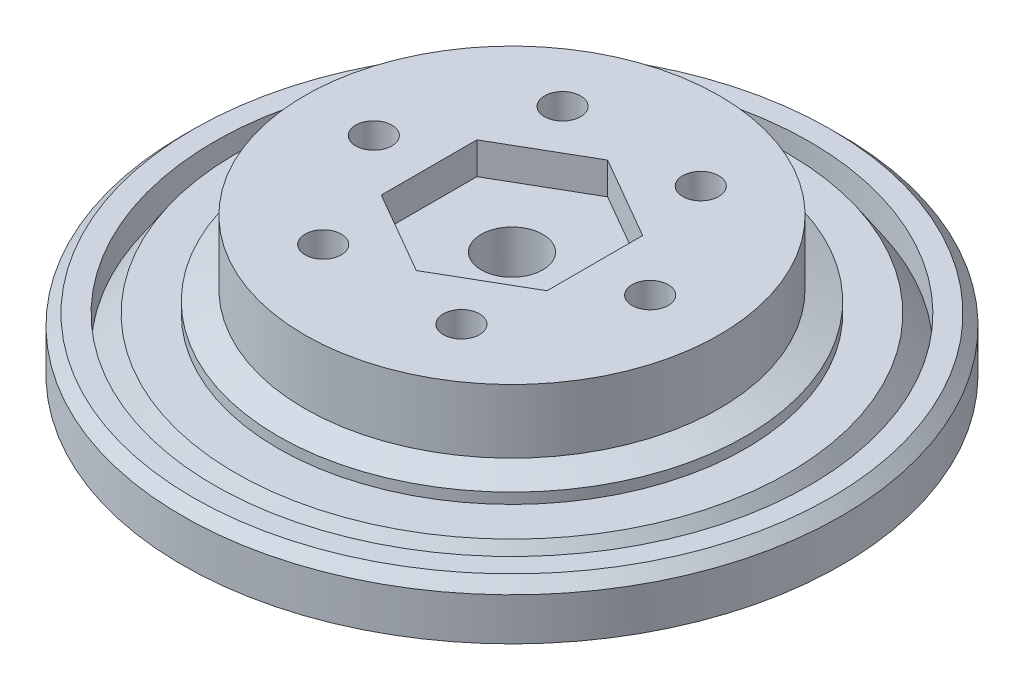
SolidWorks part; units mm, degrees
ref_plane "Спереди" through (0, 0, 0) normal (0, 0, 1) x (1, 0, 0)
ref_plane "Сверху" through (0, 0, 0) normal (0, 1, 0) x (1, 0, 0)
ref_plane "Справа" through (0, 0, 0) normal (1, 0, 0) x (0, 0, -1)
ref_axis "Ось1" through (0, -2.9945, 0) along (0, 1, 0)
sketch "Эскиз2" plane through (0, 0, 0) normal (0, 0, 1) x (1, 0, 0)
  line L0 (-19.5, 2) -> (-22, 1) construction
  line L1 (-19.5, 8) -> (-19.5, 2) construction
  line L2 (-19.5, 2) -> (-22, 1)
  line L3 (-19.5, 8) -> (-19.5, 2)
  line L4 (-22, 1) -> (-22, 0) construction
  line L5 (-22, 1) -> (-22, 0)
  line L6 (0, 0) -> (-22, 0)
  line L7 (-26, 0) -> (26, 0) construction
  line L8 (0, 8) -> (0, 0)
  line L9 (19.5, 8) -> (-19.5, 8) construction
  line L10 (0, 8) -> (-19.5, 8)
revolve "Повернуть1" add sketch "Эскиз2" angle 360 about L8
sketch "Эскиз4" plane through (0, 0, 0) normal (0, 0, 1) x (1, 0, 0)
  line L4 (0, 0) -> (26, 0)
  line L5 (0, 0) -> (0, -3)
  line L6 (26, 0) -> (26, -3) construction
  line L7 (0, -3) -> (26, -3) construction
  line L8 (26, 0) -> (28, -3)
  line L9 (28, -3) -> (26, -3) construction
  line L10 (0, -3) -> (0, -5)
  line L11 (0, -3) -> (31, -3) construction
  line L12 (0, -5) -> (31, -5)
  line L13 (31, -3) -> (31, -5)
  line L14 (28, -3) -> (31, -3)
  dimension "D1" = 3
  dimension "D2" = 2
  dimension "D3" = 2
  dimension "D4" = 3
revolve "Повернуть2" add sketch "Эскиз4" angle 360 about L10
sketch "Эскиз6" plane through (0, -5, 0) normal (0, -1, 0) x (1, 0, 0)
  line L1 (2.7472, -11.2583) -> (4.6236, -14.5083)
  line L2 (4.6236, -14.5083) -> (8.3764, -14.5083)
  line L3 (8.3764, -14.5083) -> (10.2528, -11.2583)
  line L4 (10.2528, -11.2583) -> (8.3764, -8.0083)
  line L5 (8.3764, -8.0083) -> (4.6236, -8.0083)
  line L6 (4.6236, -8.0083) -> (2.7472, -11.2583)
  line L7 (-10.2528, -11.2583) -> (-8.3764, -14.5083)
  line L8 (-8.3764, -14.5083) -> (-4.6236, -14.5083)
  line L9 (-4.6236, -14.5083) -> (-2.7472, -11.2583)
  line L10 (-2.7472, -11.2583) -> (-4.6236, -8.0083)
  line L11 (-4.6236, -8.0083) -> (-8.3764, -8.0083)
  line L12 (-8.3764, -8.0083) -> (-10.2528, -11.2583)
  line L13 (-16.7528, 0) -> (-14.8764, -3.25)
  line L14 (-14.8764, -3.25) -> (-11.1236, -3.25)
  line L15 (-11.1236, -3.25) -> (-9.2472, 0)
  line L16 (-9.2472, 0) -> (-11.1236, 3.25)
  line L17 (-11.1236, 3.25) -> (-14.8764, 3.25)
  line L18 (-14.8764, 3.25) -> (-16.7528, 0)
  line L19 (-10.2528, 11.2583) -> (-8.3764, 8.0083)
  line L20 (-8.3764, 8.0083) -> (-4.6236, 8.0083)
  line L21 (-4.6236, 8.0083) -> (-2.7472, 11.2583)
  line L22 (-2.7472, 11.2583) -> (-4.6236, 14.5083)
  line L23 (-4.6236, 14.5083) -> (-8.3764, 14.5083)
  line L24 (-8.3764, 14.5083) -> (-10.2528, 11.2583)
  line L25 (2.7472, 11.2583) -> (4.6236, 8.0083)
  line L26 (4.6236, 8.0083) -> (8.3764, 8.0083)
  line L27 (8.3764, 8.0083) -> (10.2528, 11.2583)
  line L28 (10.2528, 11.2583) -> (8.3764, 14.5083)
  line L29 (8.3764, 14.5083) -> (4.6236, 14.5083)
  line L30 (4.6236, 14.5083) -> (2.7472, 11.2583)
  line L31 (9.2472, 0) -> (11.1236, -3.25)
  line L32 (11.1236, -3.25) -> (14.8764, -3.25)
  line L33 (14.8764, -3.25) -> (16.7528, 0)
  line L34 (16.7528, 0) -> (14.8764, 3.25)
  line L35 (14.8764, 3.25) -> (11.1236, 3.25)
  line L36 (11.1236, 3.25) -> (9.2472, 0)
  circle A0 centre (-13, 0) radius 1.7 construction
  circle A1 centre (-6.5, -11.2583) radius 1.7 construction
  circle A2 centre (6.5, -11.2583) radius 1.7 construction
  circle A3 centre (13, 0) radius 1.7 construction
  circle A4 centre (6.5, 11.2583) radius 1.7 construction
  circle A5 centre (-6.5, 11.2583) radius 1.7 construction
  circle A6 centre (-13, 0) radius 1.7 construction
  circle A7 centre (-6.5, -11.2583) radius 1.7 construction
  circle A8 centre (6.5, -11.2583) radius 1.7 construction
  circle A9 centre (13, 0) radius 1.7 construction
  circle A10 centre (6.5, 11.2583) radius 1.7 construction
  circle A11 centre (-6.5, 11.2583) radius 1.7 construction
  circle A12 centre (6.5, -11.2583) radius 3.25 construction
  circle A13 centre (-6.5, -11.2583) radius 3.25 construction
  circle A14 centre (-13, 0) radius 3.25 construction
  circle A15 centre (-6.5, 11.2583) radius 3.25 construction
  circle A16 centre (6.5, 11.2583) radius 3.25 construction
  circle A17 centre (13, 0) radius 3.25 construction
  dimension "D1" = 6.5
extrude "Вырез-Вытянуть1" cut sketch "Эскиз6" against normal blind 10
hole_wizard "Отверстие с зазором M31" positions "Эскиз7" profile "Эскиз9" hole size "M3" standard "DIN" end condition through all
sketch "Эскиз7" plane through (0, 5, 0) normal (0, -1, 0) x (-1, 0, 0)
  line L0 (-4.6236, -14.5083) -> (-2.7472, -11.2583) construction
  line L1 (-2.7472, -11.2583) -> (-4.6236, -8.0083) construction
  line L2 (-4.6236, -8.0083) -> (-8.3764, -8.0083) construction
  line L3 (-8.3764, -8.0083) -> (-10.2528, -11.2583) construction
  line L4 (-10.2528, -11.2583) -> (-8.3764, -14.5083) construction
  line L5 (-8.3764, -14.5083) -> (-4.6236, -14.5083) construction
  line L6 (8.3764, -14.5083) -> (10.2528, -11.2583) construction
  line L7 (10.2528, -11.2583) -> (8.3764, -8.0083) construction
  line L8 (8.3764, -8.0083) -> (4.6236, -8.0083) construction
  line L9 (4.6236, -8.0083) -> (2.7472, -11.2583) construction
  line L10 (2.7472, -11.2583) -> (4.6236, -14.5083) construction
  line L11 (4.6236, -14.5083) -> (8.3764, -14.5083) construction
  line L12 (14.8764, -3.25) -> (16.7528, 0) construction
  line L13 (16.7528, 0) -> (14.8764, 3.25) construction
  line L14 (14.8764, 3.25) -> (11.1236, 3.25) construction
  line L15 (11.1236, 3.25) -> (9.2472, 0) construction
  line L16 (9.2472, 0) -> (11.1236, -3.25) construction
  line L17 (11.1236, -3.25) -> (14.8764, -3.25) construction
  line L18 (8.3764, 8.0083) -> (10.2528, 11.2583) construction
  line L19 (10.2528, 11.2583) -> (8.3764, 14.5083) construction
  line L20 (8.3764, 14.5083) -> (4.6236, 14.5083) construction
  line L21 (4.6236, 14.5083) -> (2.7472, 11.2583) construction
  line L22 (2.7472, 11.2583) -> (4.6236, 8.0083) construction
  line L23 (4.6236, 8.0083) -> (8.3764, 8.0083) construction
  line L24 (-4.6236, 8.0083) -> (-2.7472, 11.2583) construction
  line L25 (-2.7472, 11.2583) -> (-4.6236, 14.5083) construction
  line L26 (-4.6236, 14.5083) -> (-8.3764, 14.5083) construction
  line L27 (-8.3764, 14.5083) -> (-10.2528, 11.2583) construction
  line L28 (-10.2528, 11.2583) -> (-8.3764, 8.0083) construction
  line L29 (-8.3764, 8.0083) -> (-4.6236, 8.0083) construction
  line L30 (-11.1236, -3.25) -> (-9.2472, 0) construction
  line L31 (-9.2472, 0) -> (-11.1236, 3.25) construction
  line L32 (-11.1236, 3.25) -> (-14.8764, 3.25) construction
  line L33 (-14.8764, 3.25) -> (-16.7528, 0) construction
  line L34 (-16.7528, 0) -> (-14.8764, -3.25) construction
  line L35 (-14.8764, -3.25) -> (-11.1236, -3.25) construction
  line L36 (-4.6236, -14.5083) -> (-2.7472, -11.2583) construction
  line L37 (-2.7472, -11.2583) -> (-4.6236, -8.0083) construction
  line L38 (-4.6236, -8.0083) -> (-8.3764, -8.0083) construction
  line L39 (-8.3764, -8.0083) -> (-10.2528, -11.2583) construction
  line L40 (-10.2528, -11.2583) -> (-8.3764, -14.5083) construction
  line L41 (-8.3764, -14.5083) -> (-4.6236, -14.5083) construction
  line L42 (8.3764, -14.5083) -> (10.2528, -11.2583) construction
  line L43 (10.2528, -11.2583) -> (8.3764, -8.0083) construction
  line L44 (8.3764, -8.0083) -> (4.6236, -8.0083) construction
  line L45 (4.6236, -8.0083) -> (2.7472, -11.2583) construction
  line L46 (2.7472, -11.2583) -> (4.6236, -14.5083) construction
  line L47 (4.6236, -14.5083) -> (8.3764, -14.5083) construction
  line L48 (14.8764, -3.25) -> (16.7528, 0) construction
  line L49 (16.7528, 0) -> (14.8764, 3.25) construction
  line L50 (14.8764, 3.25) -> (11.1236, 3.25) construction
  line L51 (11.1236, 3.25) -> (9.2472, 0) construction
  line L52 (9.2472, 0) -> (11.1236, -3.25) construction
  line L53 (11.1236, -3.25) -> (14.8764, -3.25) construction
  line L54 (8.3764, 8.0083) -> (10.2528, 11.2583) construction
  line L55 (10.2528, 11.2583) -> (8.3764, 14.5083) construction
  line L56 (8.3764, 14.5083) -> (4.6236, 14.5083) construction
  line L57 (4.6236, 14.5083) -> (2.7472, 11.2583) construction
  line L58 (2.7472, 11.2583) -> (4.6236, 8.0083) construction
  line L59 (4.6236, 8.0083) -> (8.3764, 8.0083) construction
  line L60 (-4.6236, 8.0083) -> (-2.7472, 11.2583) construction
  line L61 (-2.7472, 11.2583) -> (-4.6236, 14.5083) construction
  line L62 (-4.6236, 14.5083) -> (-8.3764, 14.5083) construction
  line L63 (-8.3764, 14.5083) -> (-10.2528, 11.2583) construction
  line L64 (-10.2528, 11.2583) -> (-8.3764, 8.0083) construction
  line L65 (-8.3764, 8.0083) -> (-4.6236, 8.0083) construction
  line L66 (-11.1236, -3.25) -> (-9.2472, 0) construction
  line L67 (-9.2472, 0) -> (-11.1236, 3.25) construction
  line L68 (-11.1236, 3.25) -> (-14.8764, 3.25) construction
  line L69 (-14.8764, 3.25) -> (-16.7528, 0) construction
  line L70 (-16.7528, 0) -> (-14.8764, -3.25) construction
  line L71 (-14.8764, -3.25) -> (-11.1236, -3.25) construction
  line L72 (-10.2528, 11.2583) -> (-2.7472, 11.2583) construction
  line L74 (2.7472, 11.2583) -> (10.2528, 11.2583) construction
  line L76 (-16.7528, 0) -> (-9.2472, 0) construction
  line L78 (-10.2528, -11.2583) -> (-2.7472, -11.2583) construction
  line L80 (2.7472, -11.2583) -> (10.2528, -11.2583) construction
  line L82 (9.2472, 0) -> (16.7528, 0) construction
  point P99 (13, 0)
  point P101 (6.5, 11.2583)
  point P103 (-6.5, 11.2583)
  point P105 (-13, 0)
  point P107 (-6.5, -11.2583)
  point P109 (6.5, -11.2583)
sketch "Эскиз9" plane through (-6.5, 5, 11.2583) normal (1, 0, 0) x (0, 0, -1)
  line L0 (0, 0) -> (0, 3)
  line L1 (0, 3) -> (1.7, 3)
  line L2 (1.7, 3) -> (1.7, 0)
  line L5 (1.7, 0) -> (0, 0)
  line L11 (0, -6.35) -> (0, 107.95) construction
  dimension "Диаметр сквозного отверстия" = 3.4
  dimension "Глубина сквозного отверстия" = 3
sketch "Эскиз10" plane through (0, 0, 0) normal (0, 0, 1) x (1, 0, 0)
  line L3 (28.0083, 10) -> (-28.0083, 10) construction
  line L13 (28.0083, 10) -> (-28.0083, 10) construction
  line L14 (28, -3) -> (-28, -3) construction
  line L16 (28, -3) -> (-28, -3) construction
  line L17 (-28.0083, 10) -> (-28, -3) construction
  line L19 (-31, 0) -> (-28, 0)
  line L20 (-31, 0) -> (-31, -3)
  line L21 (-31, -3) -> (-28, -3)
  line L22 (-28, 0) -> (-28, -3)
  line L23 (-31, 0) -> (-28, -3) construction
  line L24 (-31, -3) -> (-28, 0) construction
  point P0 (-29.5, -1.5)
  point P9 (-30.5846, -0.8168)
  dimension "D1" = 3
revolve "Повернуть3" add sketch "Эскиз10" angle 360 about axis through (0, -2.9945, 0) along (0, 1, 0)
chamfer "Фаска3" distance 1 angle 45 1 edges at (0, 0, -31)
sketch "Эскиз11" plane through (0, 8, 0) normal (0, 1, 0) x (1, 0, 0)
  line L0 (-7.7942, -4.5) -> (7.7942, -4.5) construction
  line L1 (7.7942, -4.5) -> (7.7942, 4.5)
  line L2 (7.7942, 4.5) -> (0, 9)
  line L3 (0, 9) -> (-7.7942, 4.5)
  line L4 (-7.7942, 4.5) -> (-7.7942, -4.5)
  line L5 (-7.7942, -4.5) -> (0, -9)
  line L6 (0, -9) -> (7.7942, -4.5)
  circle A0 centre (0, 0) radius 7.7942 construction
  dimension "D1" = 9
extrude "Вырез-Вытянуть2" cut sketch "Эскиз11" against normal blind 3
hole_wizard "Отверстие с зазором M51" positions "Эскиз13" profile "Эскиз14" hole size "M5" standard "DIN" end condition through all
sketch "Эскиз13" plane through (0, -5, 0) normal (0, -1, 0) x (-1, 0, 0)
  point P0 (0, 0)
sketch "Эскиз14" plane through (0, -5, 0) normal (1, 0, 0) x (0, 0, -1)
  line L0 (0, 0) -> (0, 13)
  line L1 (0, 13) -> (2.9, 13)
  line L2 (2.9, 13) -> (2.9, 0)
  line L5 (2.9, 0) -> (0, 0)
  line L11 (0, -6.35) -> (0, 107.95) construction
  dimension "Диаметр сквозного отверстия" = 5.8
  dimension "Глубина сквозного отверстия" = 13
